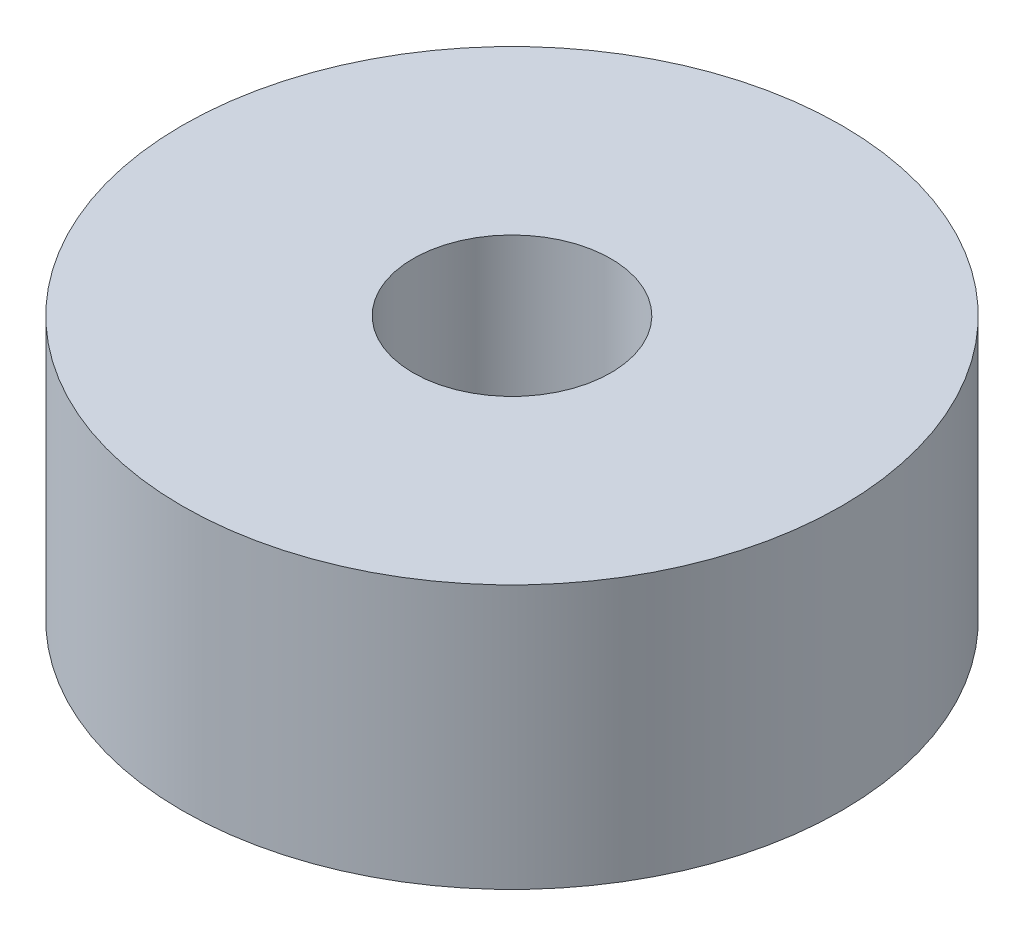
SolidWorks part; units mm, degrees
ref_plane "Front Plane" through (0, 0, 0) normal (0, 0, 1) x (1, 0, 0)
ref_plane "Top Plane" through (0, 0, 0) normal (0, 1, 0) x (1, 0, 0)
ref_plane "Right Plane" through (0, 0, 0) normal (1, 0, 0) x (0, 0, -1)
sketch "Sketch1" plane through (0, 0, 0) normal (0, 1, 0) x (1, 0, 0)
  circle A0 centre (0, 0) radius 5
  dimension "D1" = 10
extrude "Boss-Extrude1" add sketch "Sketch1" along normal blind 4
sketch "Sketch2" plane through (0, 4, 0) normal (0, 1, 0) x (1, 0, 0)
  circle A0 centre (0, 0) radius 1.5
  dimension "D1" = 3
extrude "Cut-Extrude1" cut sketch "Sketch2" against normal blind 6
